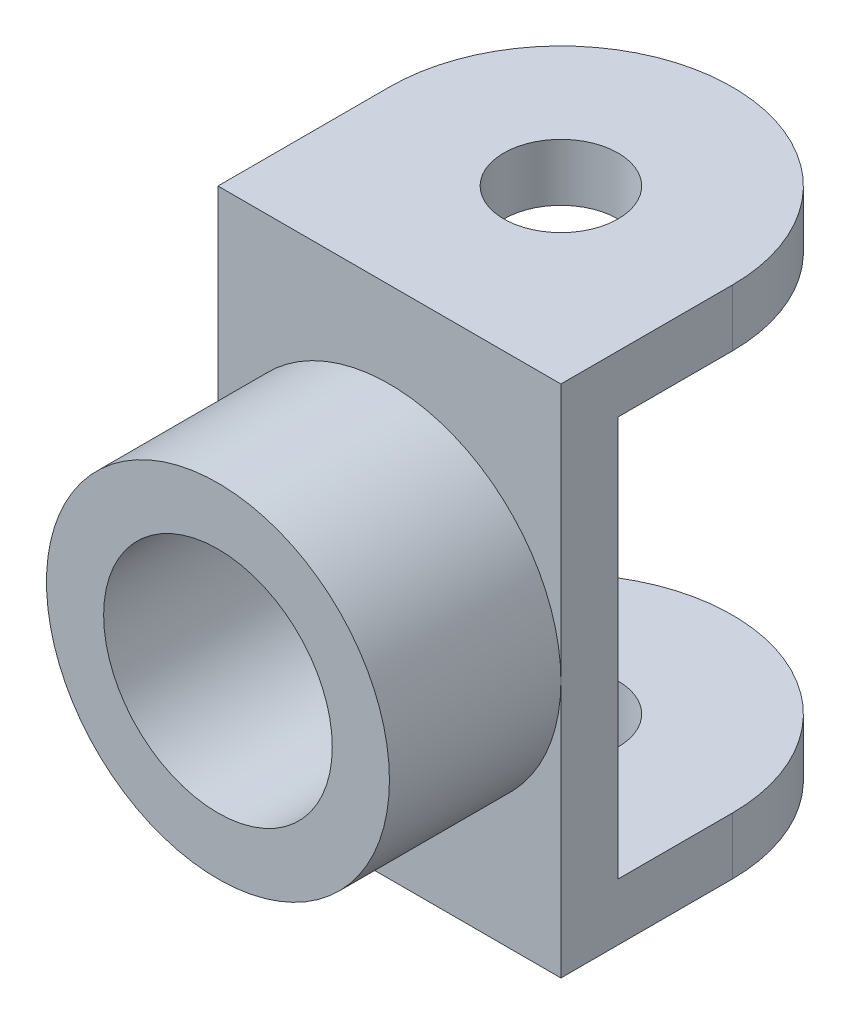
SolidWorks part; units mm, degrees
ref_plane "Front Plane" through (0, 0, 0) normal (0, 0, 1) x (1, 0, 0)
ref_plane "Top Plane" through (0, 0, 0) normal (0, 1, 0) x (1, 0, 0)
ref_plane "Right Plane" through (0, 0, 0) normal (1, 0, 0) x (0, 0, -1)
sketch "Sketch5" plane through (0, 0, 0) normal (0, 1, 0) x (1, 0, 0)
  line L0 (0, 0) -> (0, 30)
  line L1 (0, 30) -> (20, 30)
  line L2 (60, 30) -> (60, 0)
  line L3 (60, 0) -> (0, 0)
  line L4 (40, 30) -> (60, 30)
  arc A0 (60, 30) -> (0, 30) centre (30, 30) ccw
  circle A1 centre (30, 30) radius 10
  dimension "D3" = 60
  dimension "D4" = 20
  dimension "D1" = 60
  dimension "D2" = 30
extrude "Boss-Extrude4" add sketch "Sketch5" along normal blind 90 contours A1 L1 L0 L3 L2 L4 | A1 L4 A0 L1
sketch "Sketch7" plane through (0, 0, 0) normal (1, 0, 0) x (0, 0, -1)
  line L0 (10, 80) -> (10, 10)
  line L1 (10, 10) -> (65.3957, 10)
  line L2 (10, 80) -> (65.3957, 80)
  line L3 (65.3957, 80) -> (65.3957, 10)
  line L4 (0, 90) -> (0, 0) construction
  line L5 (30, 0) -> (0, 0) construction
  point P2 (0, 0)
  point P5 (0, 0)
  dimension "D1" = 10
  dimension "D2" = 70
  dimension "D3" = 10
  dimension "D4" = 55.3957
extrude "Cut-Extrude1" cut sketch "Sketch7" along normal blind 69 and the other way blind 18
sketch "Sketch8" plane through (0, 0, 0) normal (0, 0, 1) x (1, 0, 0)
  line L0 (60, 90) -> (60, 0) construction
  line L1 (60, 0) -> (0, 0) construction
  circle A0 centre (30, 45) radius 20
  circle A1 centre (30, 45) radius 30
  dimension "D1" = 60
  dimension "D2" = 40
  dimension "D3" = 30
  dimension "D4" = 45
extrude "Boss-Extrude5" add sketch "Sketch8" along normal blind 30
